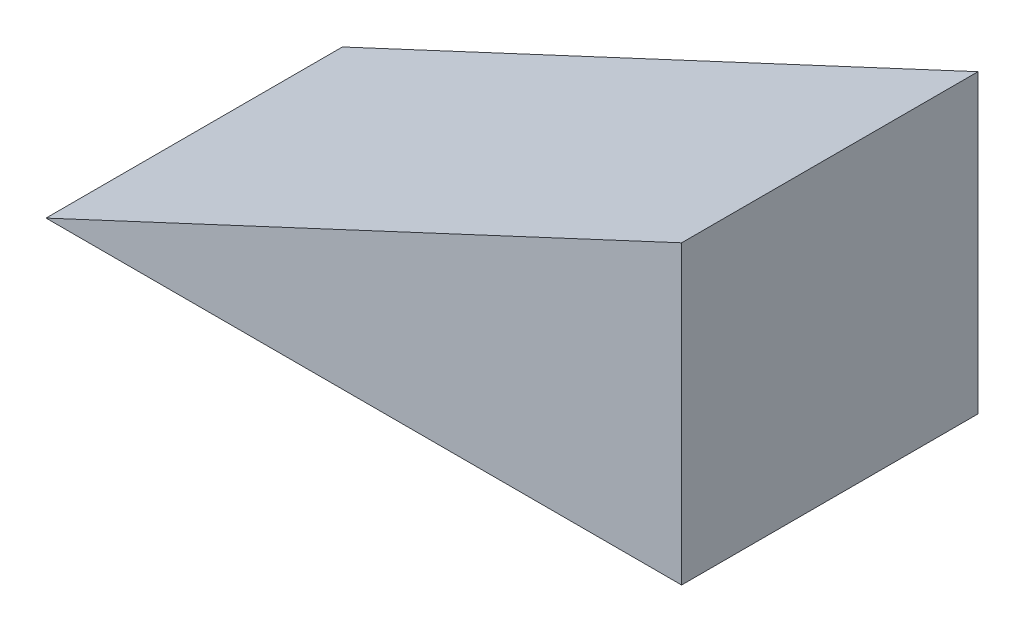
SolidWorks part; units mm, degrees
ref_plane "Ön Düzlem" through (0, 0, 0) normal (0, 0, 1) x (1, 0, 0)
ref_plane "Üst Düzlem" through (0, 0, 0) normal (0, 1, 0) x (1, 0, 0)
ref_plane "Sağ Düzlem" through (0, 0, 0) normal (1, 0, 0) x (0, 0, -1)
sketch "Çizim1" plane through (0, 0, 0) normal (0, 0, 1) x (1, 0, 0)
  line L0 (-7.6063, 3.1498) -> (35.2838, 23.1498)
  line L1 (35.2838, 23.1498) -> (35.2838, 3.1498)
  line L2 (35.2838, 3.1498) -> (-7.6063, 3.1498)
  dimension "D1" = 25
  dimension "D2" = 20
extrude "Yükseklik-Ekstrüzyon1" add sketch "Çizim1" along normal blind 20
